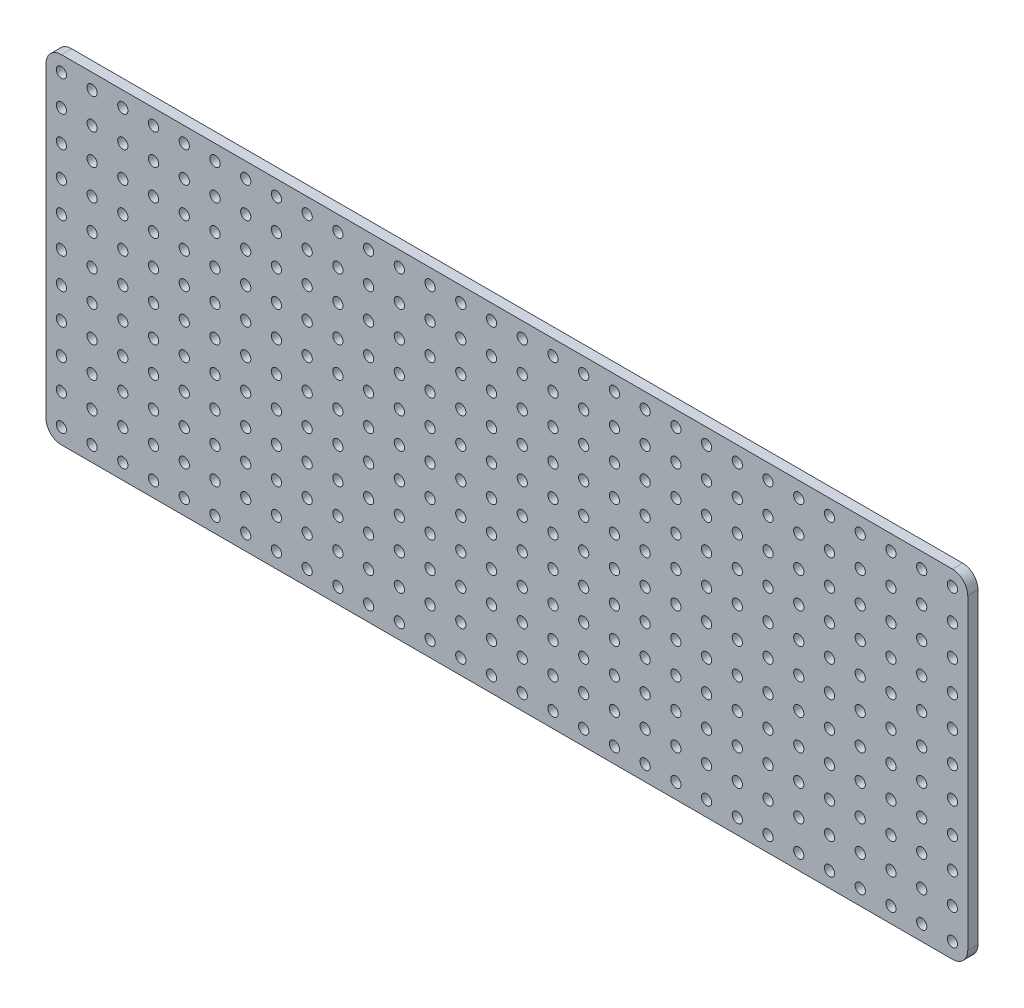
SolidWorks part; units mm, degrees
ref_plane "Alzado" through (0, 0, 0) normal (0, 0, 1) x (1, 0, 0)
ref_plane "Planta" through (0, 0, 0) normal (0, 1, 0) x (1, 0, 0)
ref_plane "Vista lateral" through (0, 0, 0) normal (1, 0, 0) x (0, 0, -1)
sketch "Model" plane through (0, 0, 0) normal (0, 0, 1) x (1, 0, 0)
  line L1 (521.9291, 485.2422) -> (521.9291, 395.2422)
  line L3 (256.4291, 489.7422) -> (517.4291, 489.7422)
  line L4 (256.4291, 390.7422) -> (517.4291, 390.7422)
  line L5 (251.9291, 485.2422) -> (251.9291, 395.2422)
  arc A0 (521.9291, 485.2422) -> (517.4291, 489.7422) centre (517.4291, 485.2422) ccw
  circle A1 centre (391.4291, 485.2422) radius 1.5
  circle A2 centre (391.4291, 476.2422) radius 1.5
  circle A3 centre (391.4291, 467.2422) radius 1.5
  circle A4 centre (391.4291, 458.2422) radius 1.5
  circle A5 centre (391.4291, 449.2422) radius 1.5
  circle A6 centre (391.4291, 440.2422) radius 1.5
  circle A7 centre (391.4291, 431.2422) radius 1.5
  circle A8 centre (391.4291, 422.2422) radius 1.5
  circle A9 centre (391.4291, 413.2422) radius 1.5
  circle A10 centre (391.4291, 404.2422) radius 1.5
  circle A11 centre (391.4291, 395.2422) radius 1.5
  circle A12 centre (400.4291, 485.2422) radius 1.5
  circle A13 centre (400.4291, 476.2422) radius 1.5
  circle A14 centre (400.4291, 467.2422) radius 1.5
  circle A15 centre (400.4291, 458.2422) radius 1.5
  circle A16 centre (400.4291, 449.2422) radius 1.5
  circle A17 centre (400.4291, 440.2422) radius 1.5
  circle A18 centre (400.4291, 431.2422) radius 1.5
  circle A19 centre (400.4291, 422.2422) radius 1.5
  circle A20 centre (400.4291, 413.2422) radius 1.5
  circle A21 centre (400.4291, 404.2422) radius 1.5
  circle A22 centre (400.4291, 395.2422) radius 1.5
  circle A23 centre (409.4291, 485.2422) radius 1.5
  circle A24 centre (409.4291, 476.2422) radius 1.5
  circle A25 centre (409.4291, 467.2422) radius 1.5
  circle A26 centre (409.4291, 458.2422) radius 1.5
  circle A27 centre (409.4291, 449.2422) radius 1.5
  circle A28 centre (409.4291, 440.2422) radius 1.5
  circle A29 centre (409.4291, 431.2422) radius 1.5
  circle A30 centre (409.4291, 422.2422) radius 1.5
  circle A31 centre (409.4291, 413.2422) radius 1.5
  circle A32 centre (409.4291, 404.2422) radius 1.5
  circle A33 centre (409.4291, 395.2422) radius 1.5
  circle A34 centre (418.4291, 485.2422) radius 1.5
  circle A35 centre (418.4291, 476.2422) radius 1.5
  circle A36 centre (418.4291, 467.2422) radius 1.5
  circle A37 centre (418.4291, 458.2422) radius 1.5
  circle A38 centre (418.4291, 449.2422) radius 1.5
  circle A39 centre (418.4291, 440.2422) radius 1.5
  circle A40 centre (418.4291, 431.2422) radius 1.5
  circle A41 centre (418.4291, 422.2422) radius 1.5
  circle A42 centre (418.4291, 413.2422) radius 1.5
  circle A43 centre (418.4291, 404.2422) radius 1.5
  circle A44 centre (418.4291, 395.2422) radius 1.5
  circle A45 centre (427.4291, 485.2422) radius 1.5
  circle A46 centre (427.4291, 476.2422) radius 1.5
  circle A47 centre (427.4291, 467.2422) radius 1.5
  circle A48 centre (427.4291, 458.2422) radius 1.5
  circle A49 centre (427.4291, 449.2422) radius 1.5
  circle A50 centre (427.4291, 440.2422) radius 1.5
  circle A51 centre (427.4291, 431.2422) radius 1.5
  circle A52 centre (427.4291, 422.2422) radius 1.5
  circle A53 centre (427.4291, 413.2422) radius 1.5
  circle A54 centre (427.4291, 404.2422) radius 1.5
  circle A55 centre (427.4291, 395.2422) radius 1.5
  circle A56 centre (436.4291, 485.2422) radius 1.5
  circle A57 centre (436.4291, 476.2422) radius 1.5
  circle A58 centre (436.4291, 467.2422) radius 1.5
  circle A59 centre (436.4291, 458.2422) radius 1.5
  circle A60 centre (436.4291, 449.2422) radius 1.5
  circle A61 centre (436.4291, 440.2422) radius 1.5
  circle A62 centre (436.4291, 431.2422) radius 1.5
  circle A63 centre (436.4291, 422.2422) radius 1.5
  circle A64 centre (436.4291, 413.2422) radius 1.5
  circle A65 centre (436.4291, 404.2422) radius 1.5
  circle A66 centre (436.4291, 395.2422) radius 1.5
  circle A67 centre (445.4291, 485.2422) radius 1.5
  circle A68 centre (445.4291, 476.2422) radius 1.5
  circle A69 centre (445.4291, 467.2422) radius 1.5
  circle A70 centre (445.4291, 458.2422) radius 1.5
  circle A71 centre (445.4291, 449.2422) radius 1.5
  circle A72 centre (445.4291, 440.2422) radius 1.5
  circle A73 centre (445.4291, 431.2422) radius 1.5
  circle A74 centre (445.4291, 422.2422) radius 1.5
  circle A75 centre (445.4291, 413.2422) radius 1.5
  circle A76 centre (445.4291, 404.2422) radius 1.5
  circle A77 centre (445.4291, 395.2422) radius 1.5
  circle A78 centre (454.4291, 485.2422) radius 1.5
  circle A79 centre (454.4291, 476.2422) radius 1.5
  circle A80 centre (454.4291, 467.2422) radius 1.5
  circle A81 centre (454.4291, 458.2422) radius 1.5
  circle A82 centre (454.4291, 449.2422) radius 1.5
  circle A83 centre (454.4291, 440.2422) radius 1.5
  circle A84 centre (454.4291, 431.2422) radius 1.5
  circle A85 centre (454.4291, 422.2422) radius 1.5
  circle A86 centre (454.4291, 413.2422) radius 1.5
  circle A87 centre (454.4291, 404.2422) radius 1.5
  circle A88 centre (454.4291, 395.2422) radius 1.5
  circle A89 centre (463.4291, 485.2422) radius 1.5
  circle A90 centre (463.4291, 476.2422) radius 1.5
  circle A91 centre (463.4291, 467.2422) radius 1.5
  circle A92 centre (463.4291, 458.2422) radius 1.5
  circle A93 centre (463.4291, 449.2422) radius 1.5
  circle A94 centre (463.4291, 440.2422) radius 1.5
  circle A95 centre (463.4291, 431.2422) radius 1.5
  circle A96 centre (463.4291, 422.2422) radius 1.5
  circle A97 centre (463.4291, 413.2422) radius 1.5
  circle A98 centre (463.4291, 404.2422) radius 1.5
  circle A99 centre (463.4291, 395.2422) radius 1.5
  circle A100 centre (472.4291, 485.2422) radius 1.5
  circle A101 centre (472.4291, 476.2422) radius 1.5
  circle A102 centre (472.4291, 467.2422) radius 1.5
  circle A103 centre (472.4291, 458.2422) radius 1.5
  circle A104 centre (472.4291, 449.2422) radius 1.5
  circle A105 centre (472.4291, 440.2422) radius 1.5
  circle A106 centre (472.4291, 431.2422) radius 1.5
  circle A107 centre (472.4291, 422.2422) radius 1.5
  circle A108 centre (472.4291, 413.2422) radius 1.5
  circle A109 centre (472.4291, 404.2422) radius 1.5
  circle A110 centre (472.4291, 395.2422) radius 1.5
  circle A111 centre (481.4291, 485.2422) radius 1.5
  circle A112 centre (481.4291, 476.2422) radius 1.5
  circle A113 centre (481.4291, 467.2422) radius 1.5
  circle A114 centre (481.4291, 458.2422) radius 1.5
  circle A115 centre (481.4291, 449.2422) radius 1.5
  circle A116 centre (481.4291, 440.2422) radius 1.5
  circle A117 centre (481.4291, 431.2422) radius 1.5
  circle A118 centre (481.4291, 422.2422) radius 1.5
  circle A119 centre (481.4291, 413.2422) radius 1.5
  circle A120 centre (481.4291, 404.2422) radius 1.5
  circle A121 centre (481.4291, 395.2422) radius 1.5
  circle A122 centre (490.4291, 485.2422) radius 1.5
  circle A123 centre (490.4291, 476.2422) radius 1.5
  circle A124 centre (490.4291, 467.2422) radius 1.5
  circle A125 centre (490.4291, 458.2422) radius 1.5
  circle A126 centre (490.4291, 449.2422) radius 1.5
  circle A127 centre (490.4291, 440.2422) radius 1.5
  circle A128 centre (490.4291, 431.2422) radius 1.5
  circle A129 centre (490.4291, 422.2422) radius 1.5
  circle A130 centre (490.4291, 413.2422) radius 1.5
  circle A131 centre (490.4291, 404.2422) radius 1.5
  circle A132 centre (490.4291, 395.2422) radius 1.5
  circle A133 centre (499.4291, 485.2422) radius 1.5
  circle A134 centre (499.4291, 476.2422) radius 1.5
  circle A135 centre (499.4291, 467.2422) radius 1.5
  circle A136 centre (499.4291, 458.2422) radius 1.5
  circle A137 centre (499.4291, 449.2422) radius 1.5
  circle A138 centre (499.4291, 440.2422) radius 1.5
  circle A139 centre (499.4291, 431.2422) radius 1.5
  circle A140 centre (499.4291, 422.2422) radius 1.5
  circle A141 centre (499.4291, 413.2422) radius 1.5
  circle A142 centre (499.4291, 404.2422) radius 1.5
  circle A143 centre (499.4291, 395.2422) radius 1.5
  circle A144 centre (508.4291, 485.2422) radius 1.5
  circle A145 centre (508.4291, 476.2422) radius 1.5
  circle A146 centre (508.4291, 467.2422) radius 1.5
  circle A147 centre (508.4291, 458.2422) radius 1.5
  circle A148 centre (508.4291, 449.2422) radius 1.5
  circle A149 centre (508.4291, 440.2422) radius 1.5
  circle A150 centre (508.4291, 431.2422) radius 1.5
  circle A151 centre (508.4291, 422.2422) radius 1.5
  circle A152 centre (508.4291, 413.2422) radius 1.5
  circle A153 centre (508.4291, 404.2422) radius 1.5
  circle A154 centre (508.4291, 395.2422) radius 1.5
  circle A155 centre (517.4291, 485.2422) radius 1.5
  circle A156 centre (517.4291, 476.2422) radius 1.5
  circle A157 centre (517.4291, 467.2422) radius 1.5
  circle A158 centre (517.4291, 458.2422) radius 1.5
  circle A159 centre (517.4291, 449.2422) radius 1.5
  circle A160 centre (517.4291, 440.2422) radius 1.5
  circle A161 centre (517.4291, 431.2422) radius 1.5
  circle A162 centre (517.4291, 422.2422) radius 1.5
  circle A163 centre (517.4291, 413.2422) radius 1.5
  circle A164 centre (517.4291, 404.2422) radius 1.5
  circle A165 centre (517.4291, 395.2422) radius 1.5
  arc A166 (517.4291, 390.7422) -> (521.9291, 395.2422) centre (517.4291, 395.2422) ccw
  circle A167 centre (256.4291, 485.2422) radius 1.5
  circle A168 centre (256.4291, 476.2422) radius 1.5
  circle A169 centre (256.4291, 467.2422) radius 1.5
  circle A170 centre (256.4291, 458.2422) radius 1.5
  circle A171 centre (256.4291, 449.2422) radius 1.5
  circle A172 centre (256.4291, 440.2422) radius 1.5
  circle A173 centre (256.4291, 431.2422) radius 1.5
  circle A174 centre (256.4291, 422.2422) radius 1.5
  circle A175 centre (256.4291, 413.2422) radius 1.5
  circle A176 centre (256.4291, 404.2422) radius 1.5
  circle A177 centre (256.4291, 395.2422) radius 1.5
  circle A178 centre (265.4291, 485.2422) radius 1.5
  circle A179 centre (265.4291, 476.2422) radius 1.5
  circle A180 centre (265.4291, 467.2422) radius 1.5
  circle A181 centre (265.4291, 458.2422) radius 1.5
  circle A182 centre (265.4291, 449.2422) radius 1.5
  circle A183 centre (265.4291, 440.2422) radius 1.5
  circle A184 centre (265.4291, 431.2422) radius 1.5
  circle A185 centre (265.4291, 422.2422) radius 1.5
  circle A186 centre (265.4291, 413.2422) radius 1.5
  circle A187 centre (265.4291, 404.2422) radius 1.5
  circle A188 centre (265.4291, 395.2422) radius 1.5
  circle A189 centre (274.4291, 485.2422) radius 1.5
  circle A190 centre (274.4291, 476.2422) radius 1.5
  circle A191 centre (274.4291, 467.2422) radius 1.5
  circle A192 centre (274.4291, 458.2422) radius 1.5
  circle A193 centre (274.4291, 449.2422) radius 1.5
  circle A194 centre (274.4291, 440.2422) radius 1.5
  circle A195 centre (274.4291, 431.2422) radius 1.5
  circle A196 centre (274.4291, 422.2422) radius 1.5
  circle A197 centre (274.4291, 413.2422) radius 1.5
  circle A198 centre (274.4291, 404.2422) radius 1.5
  circle A199 centre (274.4291, 395.2422) radius 1.5
  circle A200 centre (283.4291, 485.2422) radius 1.5
  circle A201 centre (283.4291, 476.2422) radius 1.5
  circle A202 centre (283.4291, 467.2422) radius 1.5
  circle A203 centre (283.4291, 458.2422) radius 1.5
  circle A204 centre (283.4291, 449.2422) radius 1.5
  circle A205 centre (283.4291, 440.2422) radius 1.5
  circle A206 centre (283.4291, 431.2422) radius 1.5
  circle A207 centre (283.4291, 422.2422) radius 1.5
  circle A208 centre (283.4291, 413.2422) radius 1.5
  circle A209 centre (283.4291, 404.2422) radius 1.5
  circle A210 centre (283.4291, 395.2422) radius 1.5
  circle A211 centre (292.4291, 485.2422) radius 1.5
  circle A212 centre (292.4291, 476.2422) radius 1.5
  circle A213 centre (292.4291, 467.2422) radius 1.5
  circle A214 centre (292.4291, 458.2422) radius 1.5
  circle A215 centre (292.4291, 449.2422) radius 1.5
  circle A216 centre (292.4291, 440.2422) radius 1.5
  circle A217 centre (292.4291, 431.2422) radius 1.5
  circle A218 centre (292.4291, 422.2422) radius 1.5
  circle A219 centre (292.4291, 413.2422) radius 1.5
  circle A220 centre (292.4291, 404.2422) radius 1.5
  circle A221 centre (292.4291, 395.2422) radius 1.5
  circle A222 centre (301.4291, 485.2422) radius 1.5
  circle A223 centre (301.4291, 476.2422) radius 1.5
  circle A224 centre (301.4291, 467.2422) radius 1.5
  circle A225 centre (301.4291, 458.2422) radius 1.5
  circle A226 centre (301.4291, 449.2422) radius 1.5
  circle A227 centre (301.4291, 440.2422) radius 1.5
  circle A228 centre (301.4291, 431.2422) radius 1.5
  circle A229 centre (301.4291, 422.2422) radius 1.5
  circle A230 centre (301.4291, 413.2422) radius 1.5
  circle A231 centre (301.4291, 404.2422) radius 1.5
  circle A232 centre (301.4291, 395.2422) radius 1.5
  circle A233 centre (310.4291, 485.2422) radius 1.5
  circle A234 centre (310.4291, 476.2422) radius 1.5
  circle A235 centre (310.4291, 467.2422) radius 1.5
  circle A236 centre (310.4291, 458.2422) radius 1.5
  circle A237 centre (310.4291, 449.2422) radius 1.5
  circle A238 centre (310.4291, 440.2422) radius 1.5
  circle A239 centre (310.4291, 431.2422) radius 1.5
  circle A240 centre (310.4291, 422.2422) radius 1.5
  circle A241 centre (310.4291, 413.2422) radius 1.5
  circle A242 centre (310.4291, 404.2422) radius 1.5
  circle A243 centre (310.4291, 395.2422) radius 1.5
  circle A244 centre (319.4291, 485.2422) radius 1.5
  circle A245 centre (319.4291, 476.2422) radius 1.5
  circle A246 centre (319.4291, 467.2422) radius 1.5
  circle A247 centre (319.4291, 458.2422) radius 1.5
  circle A248 centre (319.4291, 449.2422) radius 1.5
  circle A249 centre (319.4291, 440.2422) radius 1.5
  circle A250 centre (319.4291, 431.2422) radius 1.5
  circle A251 centre (319.4291, 422.2422) radius 1.5
  circle A252 centre (319.4291, 413.2422) radius 1.5
  circle A253 centre (319.4291, 404.2422) radius 1.5
  circle A254 centre (319.4291, 395.2422) radius 1.5
  circle A255 centre (328.4291, 485.2422) radius 1.5
  circle A256 centre (328.4291, 476.2422) radius 1.5
  circle A257 centre (328.4291, 467.2422) radius 1.5
  circle A258 centre (328.4291, 458.2422) radius 1.5
  circle A259 centre (328.4291, 449.2422) radius 1.5
  circle A260 centre (328.4291, 440.2422) radius 1.5
  circle A261 centre (328.4291, 431.2422) radius 1.5
  circle A262 centre (328.4291, 422.2422) radius 1.5
  circle A263 centre (328.4291, 413.2422) radius 1.5
  circle A264 centre (328.4291, 404.2422) radius 1.5
  circle A265 centre (328.4291, 395.2422) radius 1.5
  circle A266 centre (337.4291, 485.2422) radius 1.5
  circle A267 centre (337.4291, 476.2422) radius 1.5
  circle A268 centre (337.4291, 467.2422) radius 1.5
  circle A269 centre (337.4291, 458.2422) radius 1.5
  circle A270 centre (337.4291, 449.2422) radius 1.5
  circle A271 centre (337.4291, 440.2422) radius 1.5
  circle A272 centre (337.4291, 431.2422) radius 1.5
  circle A273 centre (337.4291, 422.2422) radius 1.5
  circle A274 centre (337.4291, 413.2422) radius 1.5
  circle A275 centre (337.4291, 404.2422) radius 1.5
  circle A276 centre (337.4291, 395.2422) radius 1.5
  circle A277 centre (346.4291, 485.2422) radius 1.5
  circle A278 centre (346.4291, 476.2422) radius 1.5
  circle A279 centre (346.4291, 467.2422) radius 1.5
  circle A280 centre (346.4291, 458.2422) radius 1.5
  circle A281 centre (346.4291, 449.2422) radius 1.5
  circle A282 centre (346.4291, 440.2422) radius 1.5
  circle A283 centre (346.4291, 431.2422) radius 1.5
  circle A284 centre (346.4291, 422.2422) radius 1.5
  circle A285 centre (346.4291, 413.2422) radius 1.5
  circle A286 centre (346.4291, 404.2422) radius 1.5
  circle A287 centre (346.4291, 395.2422) radius 1.5
  circle A288 centre (355.4291, 485.2422) radius 1.5
  circle A289 centre (355.4291, 476.2422) radius 1.5
  circle A290 centre (355.4291, 467.2422) radius 1.5
  circle A291 centre (355.4291, 458.2422) radius 1.5
  circle A292 centre (355.4291, 449.2422) radius 1.5
  circle A293 centre (355.4291, 440.2422) radius 1.5
  circle A294 centre (355.4291, 431.2422) radius 1.5
  circle A295 centre (355.4291, 422.2422) radius 1.5
  circle A296 centre (355.4291, 413.2422) radius 1.5
  circle A297 centre (355.4291, 404.2422) radius 1.5
  circle A298 centre (355.4291, 395.2422) radius 1.5
  circle A299 centre (364.4291, 485.2422) radius 1.5
  circle A300 centre (364.4291, 476.2422) radius 1.5
  circle A301 centre (364.4291, 467.2422) radius 1.5
  circle A302 centre (364.4291, 458.2422) radius 1.5
  circle A303 centre (364.4291, 449.2422) radius 1.5
  circle A304 centre (364.4291, 440.2422) radius 1.5
  circle A305 centre (364.4291, 431.2422) radius 1.5
  circle A306 centre (364.4291, 422.2422) radius 1.5
  circle A307 centre (364.4291, 413.2422) radius 1.5
  circle A308 centre (364.4291, 404.2422) radius 1.5
  circle A309 centre (364.4291, 395.2422) radius 1.5
  circle A310 centre (373.4291, 485.2422) radius 1.5
  circle A311 centre (373.4291, 476.2422) radius 1.5
  circle A312 centre (373.4291, 467.2422) radius 1.5
  circle A313 centre (373.4291, 458.2422) radius 1.5
  circle A314 centre (373.4291, 449.2422) radius 1.5
  circle A315 centre (373.4291, 440.2422) radius 1.5
  circle A316 centre (373.4291, 431.2422) radius 1.5
  circle A317 centre (373.4291, 422.2422) radius 1.5
  circle A318 centre (373.4291, 413.2422) radius 1.5
  circle A319 centre (373.4291, 404.2422) radius 1.5
  circle A320 centre (373.4291, 395.2422) radius 1.5
  circle A321 centre (382.4291, 485.2422) radius 1.5
  circle A322 centre (382.4291, 476.2422) radius 1.5
  circle A323 centre (382.4291, 467.2422) radius 1.5
  circle A324 centre (382.4291, 458.2422) radius 1.5
  circle A325 centre (382.4291, 449.2422) radius 1.5
  circle A326 centre (382.4291, 440.2422) radius 1.5
  circle A327 centre (382.4291, 431.2422) radius 1.5
  circle A328 centre (382.4291, 422.2422) radius 1.5
  circle A329 centre (382.4291, 413.2422) radius 1.5
  circle A330 centre (382.4291, 404.2422) radius 1.5
  circle A331 centre (382.4291, 395.2422) radius 1.5
  arc A332 (256.4291, 489.7422) -> (251.9291, 485.2422) centre (256.4291, 485.2422) ccw
  arc A333 (251.9291, 395.2422) -> (256.4291, 390.7422) centre (256.4291, 395.2422) ccw
extrude "Saliente-Extruir1" add sketch "Model" along normal blind 3
